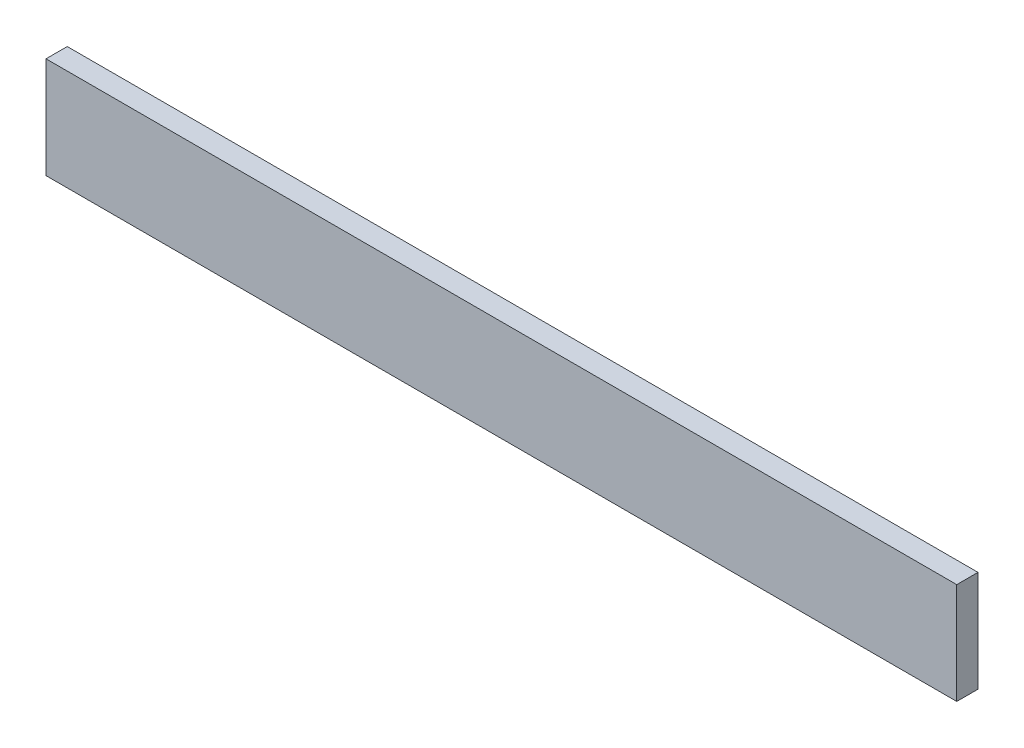
SolidWorks part; units mm, degrees
ref_plane "Front Plane" through (0, 0, 0) normal (0, 0, 1) x (1, 0, 0)
ref_plane "Top Plane" through (0, 0, 0) normal (0, 1, 0) x (1, 0, 0)
ref_plane "Right Plane" through (0, 0, 0) normal (1, 0, 0) x (0, 0, -1)
sketch "Sketch1" plane through (0, 0, 0) normal (0, 0, 1) x (1, 0, 0)
  line L1 (-228.6, 4.7978) -> (0, 4.7978)
  line L2 (-228.6, 4.7978) -> (-228.6, -20.6022)
  line L3 (-228.6, -20.6022) -> (0, -20.6022)
  line L4 (0, 4.7978) -> (0, -20.6022)
  dimension "D1" = 228.6
  dimension "D2" = 25.4
extrude "Boss-Extrude1" add sketch "Sketch1" along normal blind 5.334
